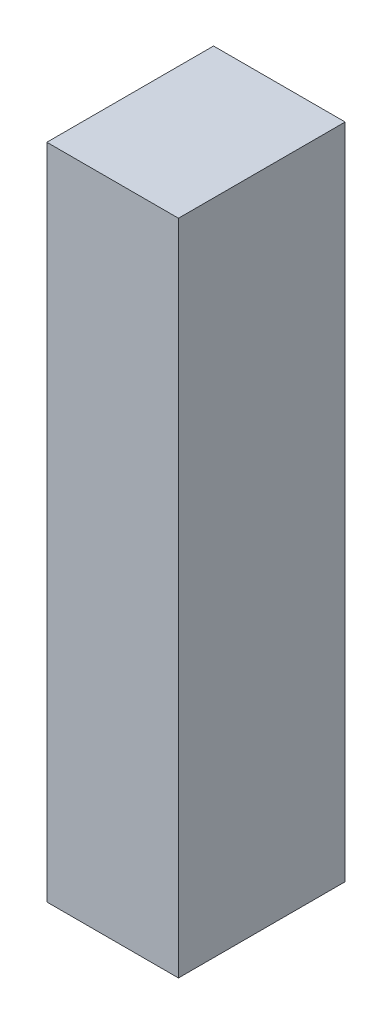
SolidWorks part; units mm, degrees
ref_plane "Front Plane" through (0, 0, 0) normal (0, 0, 1) x (1, 0, 0)
ref_plane "Top Plane" through (0, 0, 0) normal (0, 1, 0) x (1, 0, 0)
ref_plane "Right Plane" through (0, 0, 0) normal (1, 0, 0) x (0, 0, -1)
sketch "Sketch1" plane through (0, 0, 0) normal (0, 1, 0) x (1, 0, 0)
  line L1 (-7.5, -9.5) -> (7.5, -9.5)
  line L2 (-7.5, -9.5) -> (-7.5, 9.5)
  line L3 (-7.5, 9.5) -> (7.5, 9.5)
  line L4 (7.5, -9.5) -> (7.5, 9.5)
  line L5 (-7.5, -9.5) -> (7.5, 9.5) construction
  line L6 (-7.5, 9.5) -> (7.5, -9.5) construction
  point P0 (0, 0)
  dimension "D1" = 15
  dimension "D2" = 19
extrude "Boss-Extrude1" add sketch "Sketch1" along normal blind 75
